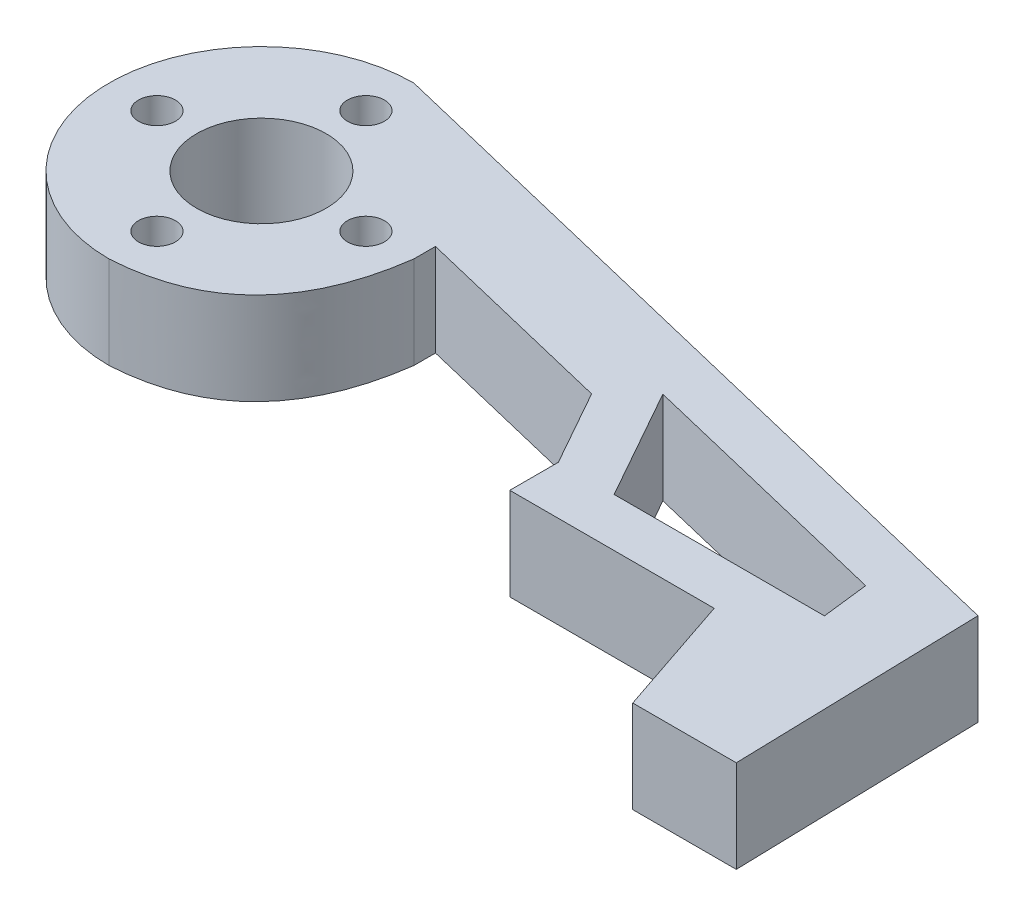
SolidWorks part; units mm, degrees
ref_plane "Front Plane" through (0, 0, 0) normal (0, 0, 1) x (1, 0, 0)
ref_plane "Top Plane" through (0, 0, 0) normal (0, 1, 0) x (1, 0, 0)
ref_plane "Right Plane" through (0, 0, 0) normal (1, 0, 0) x (0, 0, -1)
sketch "Sketch1" plane through (0, 0, 0) normal (0, 1, 0) x (1, 0, 0)
  line L0 (0, 0) -> (0, 11.314) construction
  line L1 (0, -16.5) -> (70, -16.5) construction
  line L2 (70, -16.5) -> (70, -29.7896) construction
  line L3 (70, -29.7896) -> (81.2113, -29.7896) construction
  line L4 (81.2113, -29.7896) -> (80, 16.5) construction
  line L5 (80, 16.5) -> (0, 16.5) construction
  line L6 (0, -16.5) -> (19.0878, -16.5)
  line L7 (19.0878, -16.5) -> (42.5703, -16.5)
  line L8 (42.5703, -16.5) -> (65.4349, -16.5)
  line L9 (65.4349, -16.5) -> (65.5292, -16.5)
  line L10 (65.5292, -16.5) -> (70, -29.7896)
  line L11 (70, -29.7896) -> (81.2113, -29.7896)
  line L12 (81.2113, -29.7896) -> (80.8635, -16.5)
  line L13 (80.8635, -16.5) -> (80.6411, -8)
  line L14 (80.6411, -8) -> (80.5079, -2.9108)
  line L15 (80.5079, -2.9108) -> (0, 16.5)
  circle A0 centre (0, 0) radius 7.01
  circle A1 centre (0, 11.314) radius 2
  circle A2 centre (11.314, 0) radius 2
  circle A3 centre (0, -11.314) radius 2
  circle A4 centre (-11.314, 0) radius 2
  circle A5 centre (0, 0) radius 16.5
  point P14 (0, 0)
  dimension "D1" = 14.02
  dimension "D3" = 4
  dimension "D5" = 33
  dimension "D2" = 11.314
  dimension "D6" = 70
  dimension "D7" = 80
  dimension "D4" = 4
extrude "Boss-Extrude1" add sketch "Sketch1" along normal blind 10 contours A5 L15 A0 A1 A2 A3 A4 | A5 L6 L7 L8 L9 L10 L11 L12 L13 L14 L15
sketch "Sketch2" plane through (0, 10, 0) normal (0, 1, 0) x (1, 0, 0)
  line L1 (17.6924, -11.2394) -> (72.2091, -11.2394)
  line L3 (71.6079, -6.1763) -> (17.6924, 6.8229)
  line L4 (80.5079, -2.9108) -> (0, 16.5) construction
  line L5 (0, -16.5) -> (65.5292, -16.5) construction
  line L6 (25.851, -11.2394) -> (25.851, -16.5) construction
  line L7 (33.0263, 8.5372) -> (31.7933, 3.4232) construction
  line L8 (17.6924, 6.8229) -> (17.6924, -11.2394)
  line L9 (71.6079, -6.1763) -> (72.2091, -11.2394)
  line L10 (35.6841, 2.4851) -> (43.3956, -11.2394)
  line L11 (43.3956, -11.2394) -> (49.4355, -11.2394)
  line L12 (49.4355, -11.2394) -> (42.6705, 0.8006)
  line L13 (17.6924, -11.2394) -> (17.6924, -16.5)
  line L14 (43.3956, -11.2394) -> (43.3956, -16.5)
  line L15 (16.5, 0) -> (17.6924, 0)
  line L16 (17.6924, 0) -> (17.6924, -16.5)
  line L17 (0, -16.5) -> (17.6924, -16.5)
  line L18 (38.7793, -3.0236) -> (17.6924, 2.0605)
  line L19 (16.5, 0) -> (17.6924, 0)
  line L20 (16.5, 0) -> (16.5, 6.8229)
  line L21 (16.5, 6.8229) -> (17.6924, 6.8229)
  line L22 (17.6924, 0) -> (17.6924, 6.8229)
  line L23 (25.7358, 0.1212) -> (26.8209, 4.622) construction
  line L24 (17.6924, 2.0605) -> (16.5, 2.348)
  circle A0 centre (0, 0) radius 16.5 construction
  spline S0 degree 2 poles (0, -16.5) (14.3948, -15.6568) (16.5, 0) knots 0 0 0 1 1 1
  line M13 (0, -16.5) -> (65.5292, -16.5)
extrude "Cut-Extrude1" cut sketch "Sketch2" against normal blind 10 contours L12 L1 L9 L3 | L14 L1 L13 M13 | L10 L3 L8 L1 | L8 L24 L20 L15
